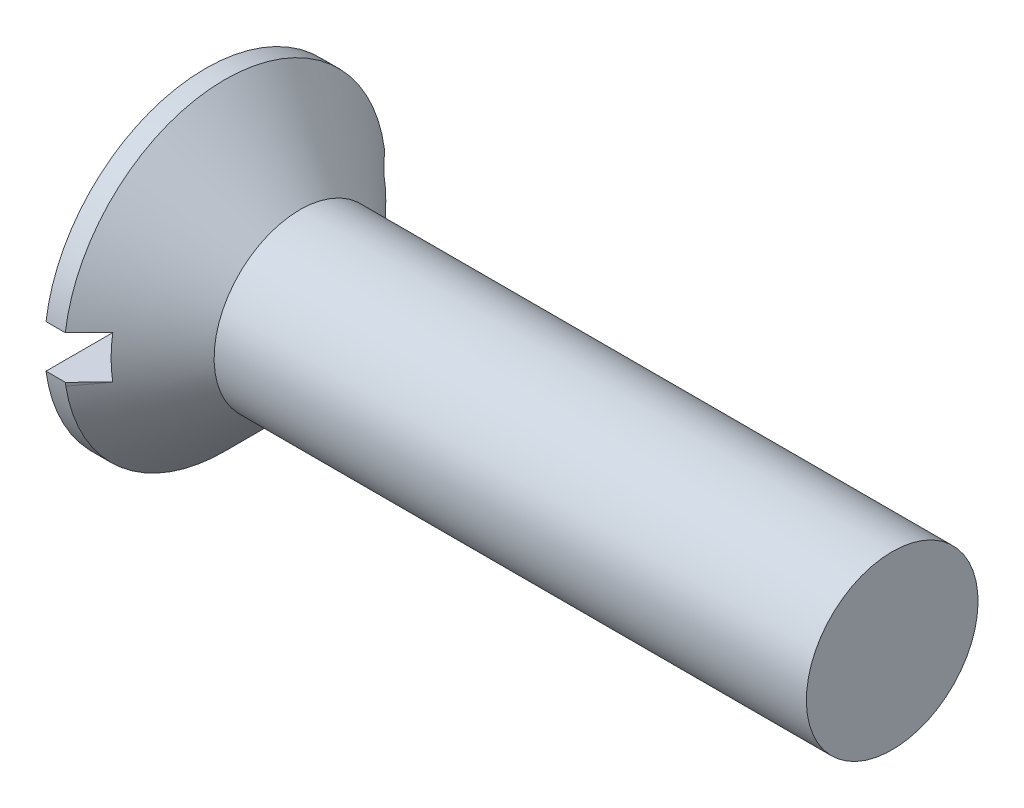
SolidWorks part; units mm, degrees
material "Plain Carbon Steel"
ref_plane "Front Plane" through (0, 0, 0) normal (0, 0, 1) x (1, 0, 0)
ref_plane "Top Plane" through (0, 0, 0) normal (0, 1, 0) x (1, 0, 0)
ref_plane "Right Plane" through (0, 0, 0) normal (1, 0, 0) x (0, 0, -1)
sketch "Sketch1" plane through (0, 0, 0) normal (0, 0, 1) x (1, 0, 0)
  line L0 (0, 0) -> (0, 3.75)
  line L1 (0, 3.75) -> (0.45, 3.75)
  line L2 (0.45, 3.75) -> (2.2, 2)
  line L3 (2.2, 2) -> (16, 2)
  line L4 (16, 2) -> (16, 0)
  line L5 (16, 0) -> (0, 0) construction
  line L6 (0, 0) -> (16, 0)
  dimension "D1" = 45
  dimension "D2" = 4
  dimension "D3" = 7.5
  dimension "D4" = 2.2
  dimension "D5" = 16
revolve "Revolve1" add sketch "Sketch1" angle 360 about L5
sketch "Sketch2" plane through (0, 0, 0) normal (-1, 0, 0) x (0, 0, 1)
  line L0 (3.75, 0) -> (-3.75, 0) construction
  line L1 (-3.75, 0.5) -> (3.75, 0.5)
  line L2 (-3.75, 0.5) -> (-3.75, -0.5)
  line L3 (-3.75, -0.5) -> (3.75, -0.5)
  line L4 (3.75, 0.5) -> (3.75, -0.5)
  circle A0 centre (0, 0) radius 3.75 construction
  dimension "D1" = 1
extrude "Cut-Extrude1" cut sketch "Sketch2" against normal blind 1
